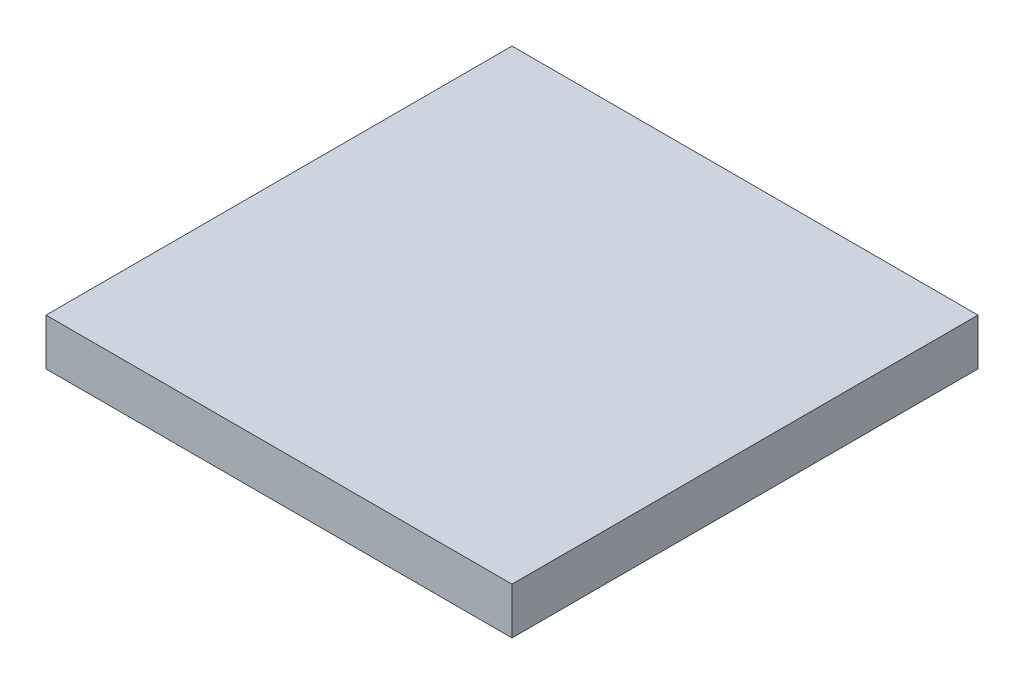
SolidWorks part; units mm, degrees
ref_plane "Front" through (0, 0, 0) normal (0, 0, 1) x (1, 0, 0)
ref_plane "Top" through (0, 0, 0) normal (0, 1, 0) x (1, 0, 0)
ref_plane "Right" through (0, 0, 0) normal (1, 0, 0) x (0, 0, -1)
sketch "Sketch1" plane through (0, 0, 0) normal (0, 1, 0) x (1, 0, 0)
  line L1 (-5, -5) -> (5, -5)
  line L2 (-5, -5) -> (-5, 5)
  line L3 (-5, 5) -> (5, 5)
  line L4 (5, -5) -> (5, 5)
  line L5 (-5, -5) -> (5, 5) construction
  line L6 (-5, 5) -> (5, -5) construction
  point P0 (0, 0)
  dimension "D1" = 10
  dimension "D2" = 10
extrude "Boss-Extrude1" add sketch "Sketch1" along normal blind 1
sketch "Sketch2" plane through (0, 1, 0) normal (0, 1, 0) x (1, 0, 0)
  point P0 (0, 0)
equation "\"xDim\"= 10"
equation "\"yDim\"= 10"
equation "\"D2@Sketch1\"=\"xDim\""
equation "\"height\"=1"
equation "\"D1@Boss-Extrude1\"=\"height\""
